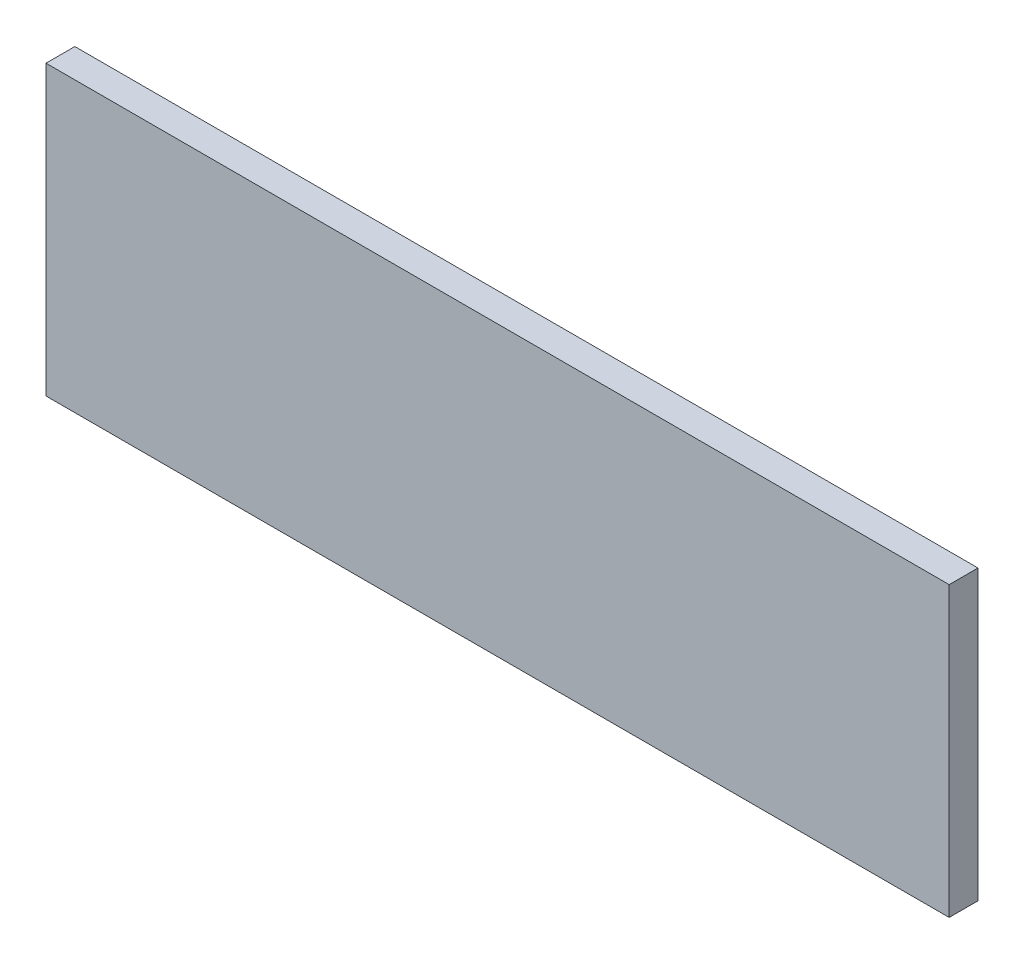
SolidWorks part; units mm, degrees
ref_plane "Plan de face" through (0, 0, 0) normal (0, 0, 1) x (1, 0, 0)
ref_plane "Plan de dessus" through (0, 0, 0) normal (0, 1, 0) x (1, 0, 0)
ref_plane "Plan de droite" through (0, 0, 0) normal (1, 0, 0) x (0, 0, -1)
sketch "Esquisse1" plane through (0, 0, 0) normal (0, 0, 1) x (1, 0, 0)
  line L1 (94, -30) -> (-94, -30)
  line L2 (94, -30) -> (94, 30)
  line L3 (94, 30) -> (-94, 30)
  line L4 (-94, -30) -> (-94, 30)
  line L5 (94, -30) -> (-94, 30) construction
  line L6 (94, 30) -> (-94, -30) construction
  point P0 (0, 0)
  dimension "D1" = 60
  dimension "D2" = 188
extrude "Boss.-Extru.1" add sketch "Esquisse1" along normal blind 6
